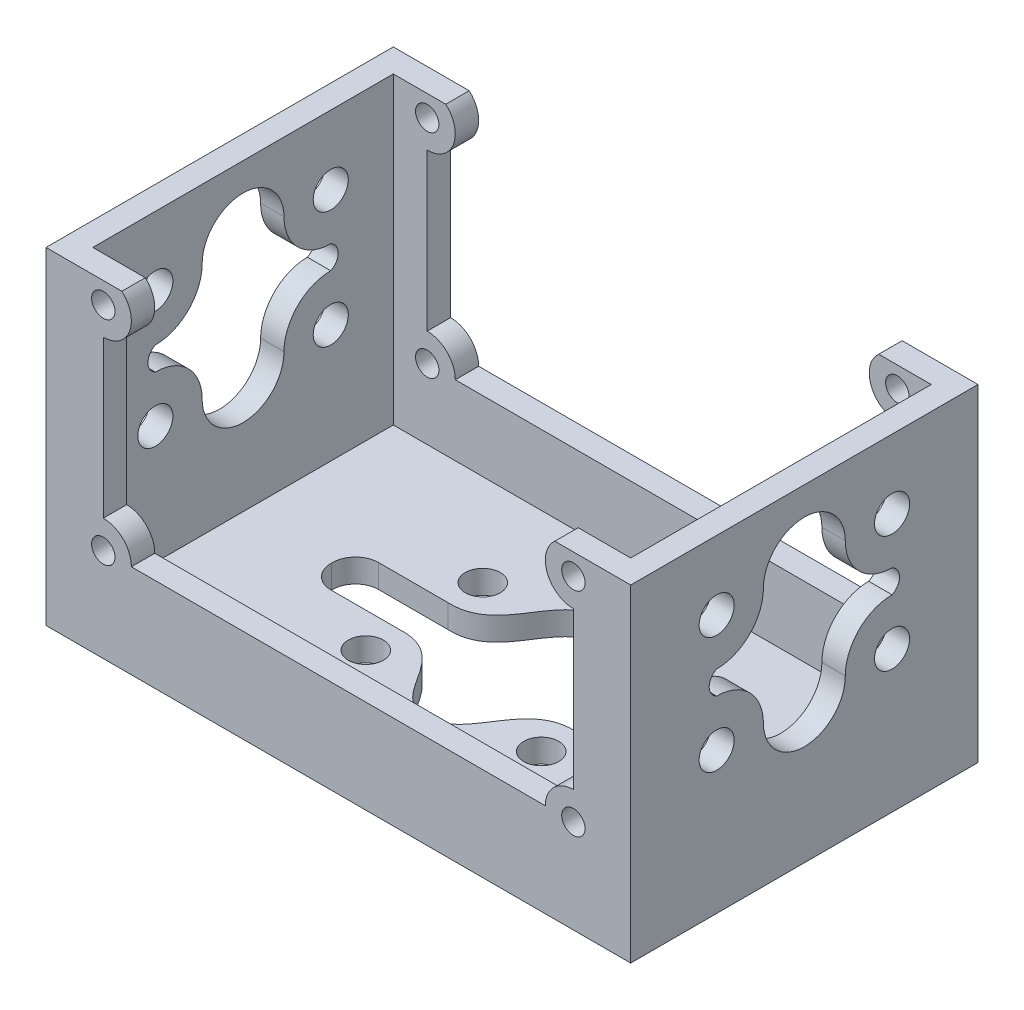
SolidWorks part; units mm, degrees
ref_plane "前视基准面" through (0, 0, 0) normal (0, 0, 1) x (1, 0, 0)
ref_plane "上视基准面" through (0, 0, 0) normal (0, 1, 0) x (1, 0, 0)
ref_plane "右视基准面" through (0, 0, 0) normal (1, 0, 0) x (0, 0, -1)
other "Configuration Table"
sketch "草图1" plane through (0, 0, 0) normal (0, 1, 0) x (1, 0, 0)
  line L1 (-25, 14.85) -> (25, 14.85)
  line L2 (-25, 14.85) -> (-25, -14.85)
  line L3 (-25, -14.85) -> (25, -14.85)
  line L4 (25, 14.85) -> (25, -14.85)
  line L5 (-25, 14.85) -> (25, -14.85) construction
  line L6 (-25, -14.85) -> (25, 14.85) construction
  point P0 (0, 0)
  dimension "D1" = 29.7
  dimension "D2" = 50
extrude "凸台-拉伸1" add sketch "草图1" along normal blind 2
sketch "草图2" plane through (0, 2, 0) normal (0, 1, 0) x (1, 0, 0)
  line L4 (23, -12.85) -> (23, 12.85)
  line L5 (23, 12.85) -> (-23, 12.85)
  line L6 (-23, 12.85) -> (-23, -12.85)
  line L7 (-23, -12.85) -> (23, -12.85)
  line L8 (25, -14.85) -> (25, 14.85)
  line L9 (25, 14.85) -> (-25, 14.85)
  line L10 (-25, 14.85) -> (-25, -14.85)
  line L11 (-25, -14.85) -> (25, -14.85)
  line L12 (25, -14.85) -> (25, 14.85)
  line L13 (25, 14.85) -> (-25, 14.85)
  line L14 (-25, 14.85) -> (-25, -14.85)
  line L15 (-25, -14.85) -> (25, -14.85)
  dimension "D3" = 2
  dimension "D1" = 0
  dimension "D2" = 2
extrude "凸台-拉伸2" add sketch "草图2" along normal blind 26
sketch "草图3" plane through (0, 0, 14.85) normal (0, 0, 1) x (1, 0, 0)
  line L0 (0, 0) -> (0, 2) construction
  line L1 (0, 2) -> (-22.5, 2) construction
  line L2 (0, 2) -> (22.5, 2) construction
  line L3 (0, 2) -> (-20.1, 2) construction
  line L4 (0, 2) -> (20.1, 2) construction
  line L5 (-20.1, 2) -> (-20.1, 8) construction
  line L6 (20.1, 2) -> (20.1, 8) construction
  line L8 (-17.7, 8) -> (17.7, 8)
  line L10 (-22.5, 2) -> (-22.5, 0)
  line L11 (-25, 0) -> (25, 0) construction
  line L14 (-18.5125, 28) -> (18.5125, 28)
  line L17 (22.5, 0) -> (22.5, 2)
  line L18 (-20.1, 17.1) -> (20.1, 17.1) construction
  line L21 (-20.1, 23.8) -> (-20.1, 10.4)
  line L22 (20.1, 23.8) -> (20.1, 10.4)
  circle A0 centre (-20.1, 8) radius 1
  circle A1 centre (20.1, 8) radius 1
  arc A2 (-20.1, 10.4) -> (-17.7, 8) centre (-20.1, 8) cw
  arc A3 (20.1, 10.4) -> (17.7, 8) centre (20.1, 8) ccw
  circle A4 centre (20.1, 26.2) radius 1
  circle A5 centre (-20.1, 26.2) radius 1
  arc A6 (-20.1, 23.8) -> (-18.5125, 28) centre (-20.1, 26.2) ccw
  arc A7 (18.5125, 28) -> (20.1, 23.8) centre (20.1, 26.2) ccw
  point P12 (-17.7, 8)
  point P15 (-20.1, 10.4)
  point P18 (0, 8)
  line M13 (25, 28) -> (-25, 28)
  dimension "D7" = 2
  dimension "D9" = 2
  dimension "D14" = 4.8
  dimension "D15" = 4.8
  dimension "D1" = 2
  dimension "D2" = 22.5
  dimension "D3" = 22.5
  dimension "D4" = 20.1
  dimension "D5" = 20.1
  dimension "D6" = 6
  dimension "D8" = 6
  dimension "D11" = 2.4
  dimension "D12" = 2.4
  dimension "D13" = 15.1
sketch "草图4" plane through (25, 0, 0) normal (1, 0, 0) x (0, 0, -1)
  line L0 (0, 0) -> (0, 2) construction
  line L1 (0, 2) -> (-7.5, 2) construction
  line L2 (0, 2) -> (7.5, 2) construction
  line L3 (-7.5, 2) -> (-7.5, 12.1) construction
  line L4 (-7.5, 12.1) -> (-7.5, 22.1) construction
  line L5 (-7.5, 22.1) -> (-3.5, 22.1) construction
  line L6 (-7.5, 22.1) -> (-7.5, 18.1) construction
  line L7 (-7.5, 17.1) -> (7.5, 17.1) construction
  line L8 (0, 22.1) -> (0, 12.1) construction
  circle A0 centre (-7.5, 12.1) radius 1.5
  circle A1 centre (-7.5, 22.1) radius 1.5
  circle A2 centre (7.5, 12.1) radius 1.5
  circle A3 centre (7.5, 22.1) radius 1.5
  arc A4 (-7.5, 18.1) -> (-3.5, 22.1) centre (-7.5, 22.1) ccw
  circle A5 centre (-7.5, 22.1) radius 4 construction
  arc A6 (-7.5, 16.1) -> (-3.5, 12.1) centre (-7.5, 12.1) cw
  arc A7 (7.5, 16.1) -> (3.5, 12.1) centre (7.5, 12.1) ccw
  arc A8 (7.5, 18.1) -> (3.5, 22.1) centre (7.5, 22.1) cw
  arc A9 (-7.5, 18.1) -> (-7.5, 16.1) centre (-7.0308, 17.1) ccw
  arc A10 (-3.5, 22.1) -> (3.5, 22.1) centre (0, 22.1) cw
  arc A11 (-3.5, 12.1) -> (3.5, 12.1) centre (0, 12.1) ccw
  arc A12 (7.5, 18.1) -> (7.5, 16.1) centre (7.0308, 17.1) cw
  dimension "D5" = 3
  dimension "D7" = 3
  dimension "D1" = 2
  dimension "D2" = 7.5
  dimension "D3" = 7.5
  dimension "D4" = 10.1
  dimension "D6" = 10
  dimension "D8" = 2.5
extrude "切除-拉伸2" cut sketch "草图4" against normal blind 2
mirror "镜向2" about plane through (0, 0, 0) normal (1, 0, 0) of "切除-拉伸2"
sketch "草图5" plane through (0, 0, 0) normal (0, -1, 0) x (1, 0, 0)
  line L0 (0, 14.85) -> (0, -14.85) construction
  line L1 (-25, 14.85) -> (25, 14.85) construction
  line L2 (25, -14.85) -> (-25, -14.85) construction
  line L3 (-25, 0) -> (25, 0) construction
  line L4 (-25, -14.85) -> (-25, 14.85) construction
  line L5 (25, 14.85) -> (25, -14.85) construction
  line L6 (7.5, 2.0335) -> (13.4458, 2.0335)
  line L7 (7.5, -2.0335) -> (13.4458, -2.0335)
  line L8 (-7.5, -2.0335) -> (-13.4458, -2.0335)
  line L9 (-7.5, 2.0335) -> (-13.4458, 2.0335)
  circle A0 centre (7.5, 5) radius 1.5
  arc A1 (13.4458, 2.0335) -> (15.4155, 0) centre (13.4458, 0.0627) cw
  arc A2 (13.4458, -2.0335) -> (15.4155, 0) centre (13.4458, -0.0627) ccw
  circle A3 centre (7.5, -5) radius 1.5
  circle A4 centre (-7.5, -5) radius 1.5
  arc A5 (-13.4458, -2.0335) -> (-15.4155, 0) centre (-13.4458, -0.0627) cw
  arc A6 (-13.4458, 2.0335) -> (-15.4155, 0) centre (-13.4458, 0.0627) ccw
  circle A7 centre (-7.5, 5) radius 1.5
  spline S0 degree 3 poles (0, 7.2301) (3.3413, 7.5781) (3.0298, 1.842) (7.5, 2.0335) knots 0 0 0 0 1 1 1 1
  spline S1 degree 3 poles (0, -7.2301) (3.3413, -7.5781) (3.0298, -1.842) (7.5, -2.0335) knots 0 0 0 0 1 1 1 1
  spline S2 degree 3 poles (0, -7.2301) (-3.3413, -7.5781) (-3.0298, -1.842) (-7.5, -2.0335) knots 0 0 0 0 1 1 1 1
  spline S3 degree 3 poles (0, 7.2301) (-3.3413, 7.5781) (-3.0298, 1.842) (-7.5, 2.0335) knots 0 0 0 0 1 1 1 1
  point P0 (7.5, 5)
  point P16 (7.5, 2.0335)
  point P19 (0, 7.2301)
  point P25 (14.8613, 1.4339)
  point P34 (14.8613, -1.4339)
  point P35 (0, -7.2301)
  point P36 (7.5, -2.0335)
  point P37 (7.5, -5)
  point P53 (-7.5, -5)
  point P54 (-7.5, -2.0335)
  point P55 (-14.8613, -1.4339)
  point P56 (-14.8613, 1.4339)
  point P57 (-7.5, 2.0335)
  point P58 (-7.5, 5)
  dimension "D3" = 3
  dimension "D1" = 5
  dimension "D2" = 7.5
extrude "切除-拉伸3" cut sketch "草图5" against normal blind 2
extrude "切除-拉伸5" cut sketch "草图3" against normal blind 2 contours A7 A6 L21 A2 L8 A3 L22 M13 | A0 | A1 | A4 | A5
mirror "镜向4" about plane through (0, 0, 0) normal (0, 0, 1) of "切除-拉伸5"
